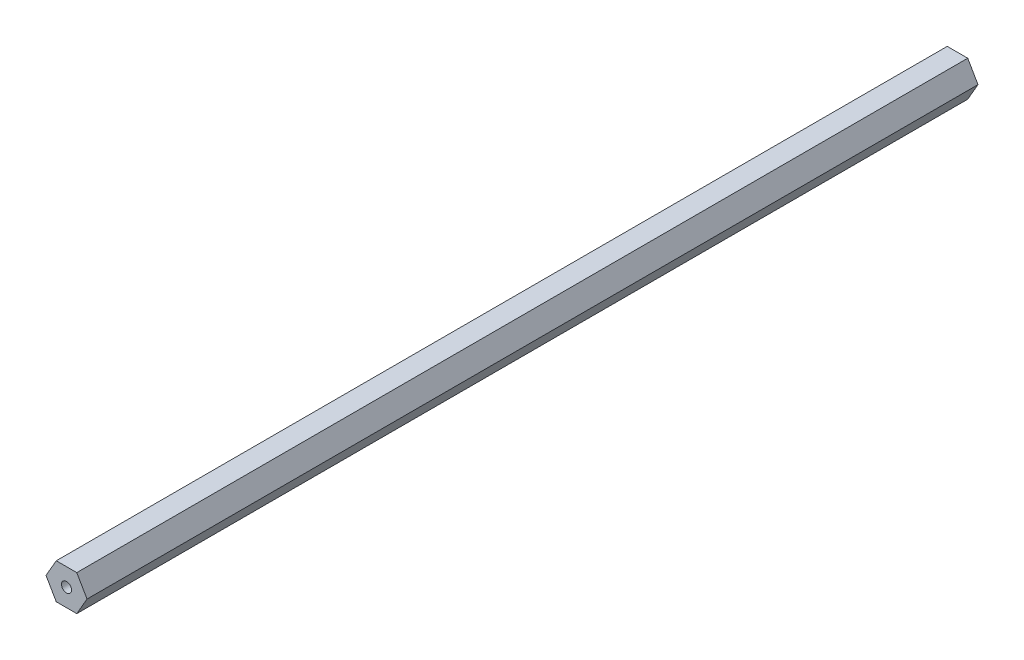
SolidWorks part; units mm, degrees
material "轻木"
ref_plane "前视基准面" through (0, 0, 0) normal (0, 0, 1) x (1, 0, 0)
ref_plane "上视基准面" through (0, 0, 0) normal (0, 1, 0) x (1, 0, 0)
ref_plane "右视基准面" through (0, 0, 0) normal (1, 0, 0) x (0, 0, -1)
sketch "草图1" plane through (0, 0, 0) normal (0, 0, 1) x (1, 0, 0)
  line L1 (4.0992, 0) -> (2.0496, 3.55)
  line L2 (2.0496, 3.55) -> (-2.0496, 3.55)
  line L3 (-2.0496, 3.55) -> (-4.0992, 0)
  line L4 (-4.0992, 0) -> (-2.0496, -3.55)
  line L5 (-2.0496, -3.55) -> (2.0496, -3.55)
  line L6 (2.0496, -3.55) -> (4.0992, 0)
  circle A0 centre (0, 0) radius 3.55 construction
  dimension "D1" = 7.1
extrude "凸台-拉伸1" add sketch "草图1" along normal blind 178
sketch "草图2" plane through (0, 0, 178) normal (0, 0, 1) x (1, 0, 0)
  circle A0 centre (0, 0) radius 1
  dimension "D1" = 2
extrude "切除-拉伸1" cut sketch "草图2" against normal blind 178
